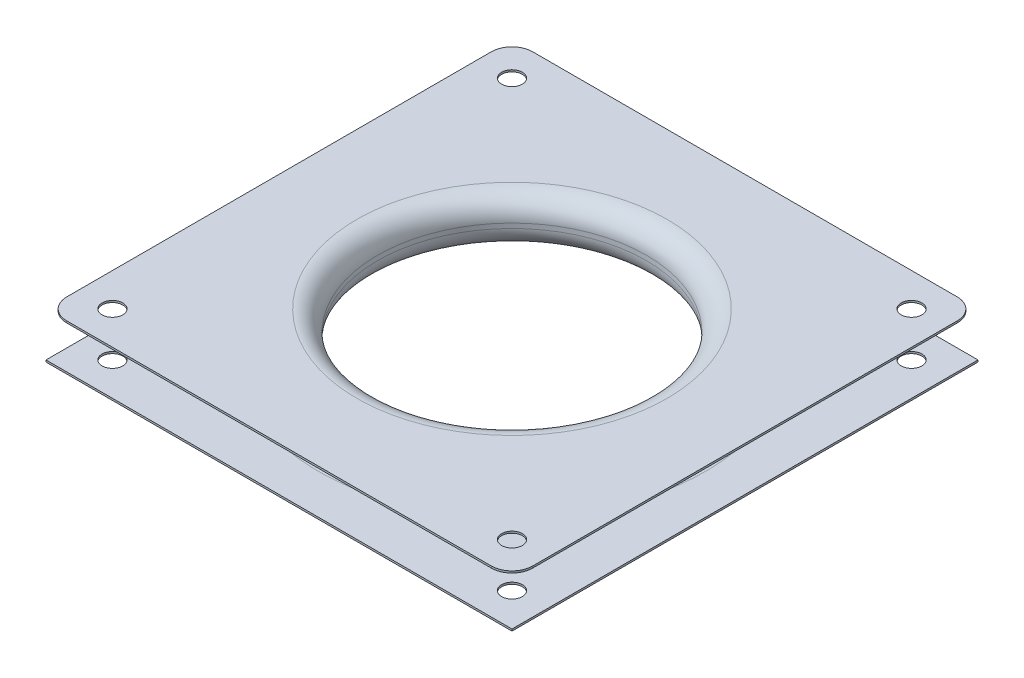
SolidWorks part; units mm, degrees
ref_plane "Plan de face" through (0, 0, 0) normal (0, 0, 1) x (1, 0, 0)
ref_plane "Plan de dessus" through (0, 0, 0) normal (0, 1, 0) x (1, 0, 0)
ref_plane "Plan de droite" through (0, 0, 0) normal (1, 0, 0) x (0, 0, -1)
sketch "Sketch1" plane through (0, 0, 0) normal (0, 1, 0) x (1, 0, 0)
  line L1 (-47.25, -47.25) -> (47.25, -47.25)
  line L2 (-47.25, -47.25) -> (-47.25, 47.25)
  line L3 (-47.25, 47.25) -> (47.25, 47.25)
  line L4 (47.25, -47.25) -> (47.25, 47.25)
  line L5 (-47.25, -47.25) -> (47.25, 47.25) construction
  line L6 (-47.25, 47.25) -> (47.25, -47.25) construction
  line L7 (-40.513, -40.513) -> (40.513, -40.513) construction
  line L8 (-40.513, -40.513) -> (-40.513, 40.513) construction
  line L9 (-40.513, 40.513) -> (40.513, 40.513) construction
  line L10 (40.513, -40.513) -> (40.513, 40.513) construction
  line L11 (-40.513, -40.513) -> (40.513, 40.513) construction
  line L12 (-40.513, 40.513) -> (40.513, -40.513) construction
  circle A0 centre (0, 0) radius 27.25
  circle A1 centre (-40.513, 40.513) radius 2.1
  circle A2 centre (40.513, 40.513) radius 2.1
  circle A3 centre (40.513, -40.513) radius 2.1
  circle A4 centre (-40.513, -40.513) radius 2.1
  point P0 (0, 0)
  dimension "D2" = 54.5
  dimension "D5" = 4.2
  dimension "D6" = 4.2
  dimension "D7" = 4.2
  dimension "D8" = 4.2
  dimension "D1" = 94.5
  dimension "D3" = 81.026
  dimension "D4" = 81.026
extrude "Boss-Extrude1" add sketch "Sketch1" along normal blind 9.35
ref_axis "Axis1" through (0, 9.35, 0) along (0, -1, 0)
sketch "Sketch3" plane through (0, 0, 0) normal (0, 0, 1) x (1, 0, 0)
  line L0 (-47.25, 9.35) -> (-47.25, 0) construction
  line L1 (-47.25, 9.35) -> (-47.25, 0) construction
  line L2 (-47.25, 8.969) -> (-35, 8.969)
  line L3 (-35, 8.969) -> (-35, 0.381)
  line L4 (-35, 0.381) -> (-47.25, 0.381)
  line L5 (-47.25, 4.675) -> (46.5148, 4.675) construction
  line L6 (47.25, 9.35) -> (-47.25, 9.35) construction
  line L7 (-47.25, 8.969) -> (-68.7142, 8.969)
  line L8 (-68.7142, 8.969) -> (-68.7142, 0.381)
  line L9 (-68.7142, 0.381) -> (-47.25, 0.381)
  point P8 (-47.25, 4.675)
  point P9 (-35, 4.675)
  dimension "D1" = 0.381
  dimension "D2" = 35
revolve "Cut-Revolve1" cut sketch "Sketch3" angle 360 about axis through (0, 9.35, 0) along (0, -1, 0)
fillet "Fillet1" radius 4.2 8 edges at (-47.25, 9.1595, -47.25) (47.25, 9.1595, -47.25) (47.25, 9.1595, 47.25) (-47.25, 9.1595, 47.25) (0, 0, 27.25) (0, 9.35, 27.25) (0, 0.381, 35) (0, 8.969, 35)
